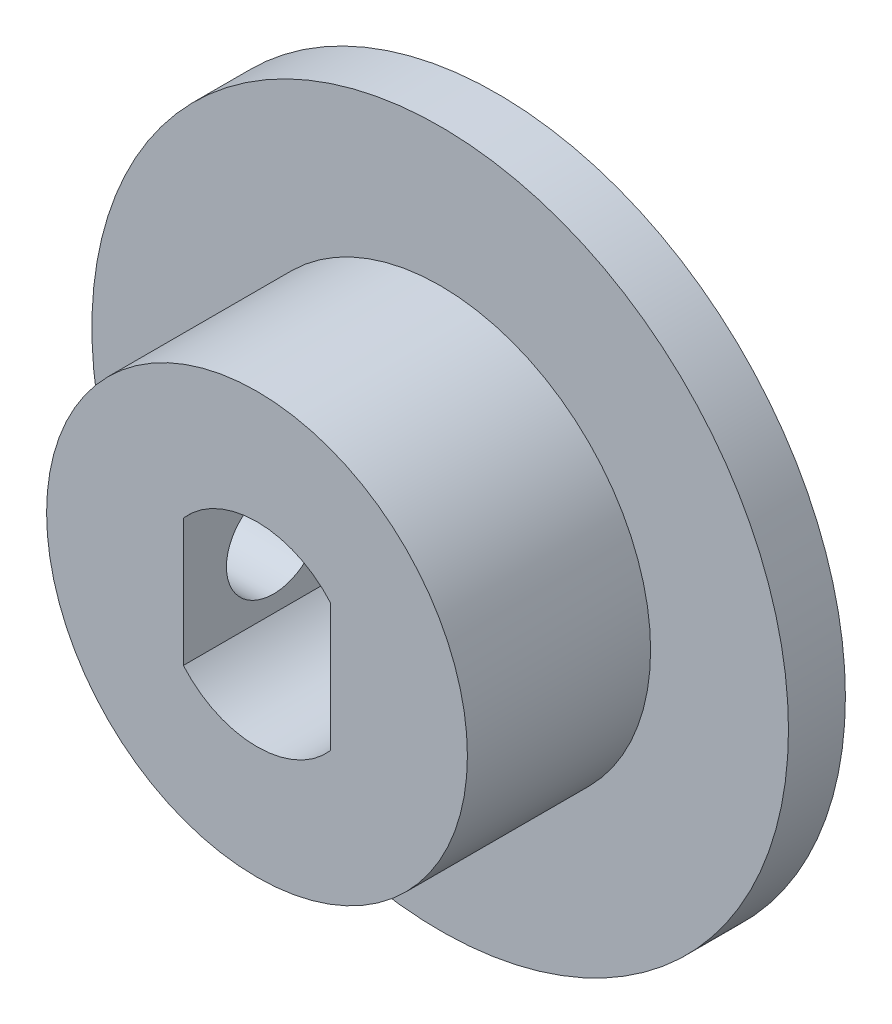
SolidWorks part; units mm, degrees
ref_plane "Front Plane" through (0, 0, 0) normal (0, 0, 1) x (1, 0, 0)
ref_plane "Top Plane" through (0, 0, 0) normal (0, 1, 0) x (1, 0, 0)
ref_plane "Right Plane" through (0, 0, 0) normal (1, 0, 0) x (0, 0, -1)
sketch "Sketch1" plane through (0, 0, 0) normal (0, 0, 1) x (1, 0, 0)
  circle A0 centre (0, 0) radius 17.8689
  dimension "D1" = 35.7378
extrude "Boss-Extrude1" add sketch "Sketch1" along normal blind 2.921
sketch "Sketch2" plane through (0, 0, 2.921) normal (0, 0, 1) x (1, 0, 0)
  circle A0 centre (0, 0) radius 10.795
  dimension "D1" = 21.59
extrude "Boss-Extrude2" add sketch "Sketch2" along normal blind 9.398
sketch "Sketch3" plane through (0, 0, 12.319) normal (0, 0, 1) x (1, 0, 0)
  line L2 (-3.7783, -3.2749) -> (-3.7783, 3.2749)
  line L4 (3.7782, -3.2749) -> (3.7782, 3.2749)
  arc A0 (-3.7783, -3.2749) -> (3.7782, -3.2749) centre (0, 0) ccw
  arc A1 (3.7782, 3.2749) -> (-3.7783, 3.2749) centre (0, 0) ccw
  dimension "D2" = 10
  dimension "D1" = 7.5565
extrude "Cut-Extrude1" cut sketch "Sketch3" against normal through all
sketch "Sketch4" plane through (0, 0, 0) normal (1, 0, 0) x (0, 0, -1)
  line L0 (-12.319, 10.795) -> (-12.319, -10.795) construction
  circle A0 centre (-7.6962, 0) radius 2.413
  dimension "D1" = 4.826
  dimension "D2" = 4.6228
extrude "Cut-Extrude2" cut sketch "Sketch4" against normal blind 16.002
